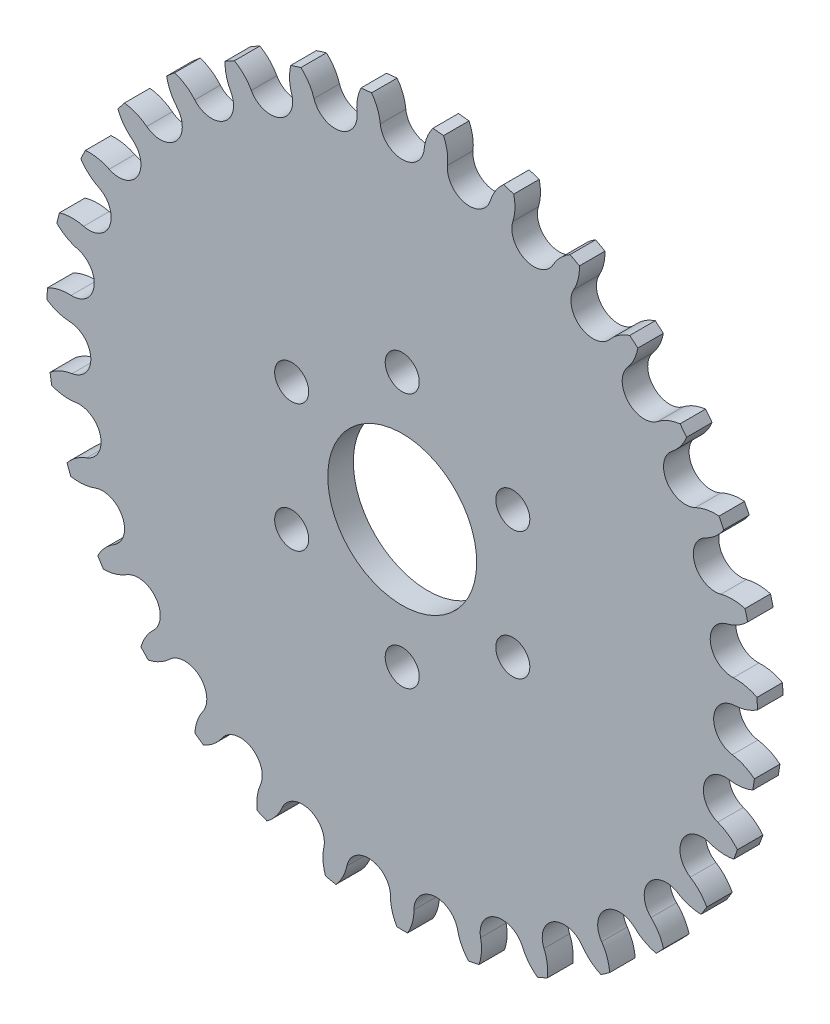
SolidWorks part; units mm, degrees
material "AISI 1020"
ref_plane "Спереди" through (0, 0, 0) normal (0, 0, 1) x (1, 0, 0)
ref_plane "Сверху" through (0, 0, 0) normal (0, 1, 0) x (1, 0, 0)
ref_plane "Справа" through (0, 0, 0) normal (1, 0, 0) x (0, 0, -1)
sketch "Эскиз1" plane through (0, 0, 0) normal (0, 0, 1) x (1, 0, 0)
  line L0 (0, 0) -> (0, 85) construction
  line L1 (0, 85) -> (15.8056, 83.5176) construction
  line L2 (15.8056, 83.5176) -> (0, 0) construction
  line L3 (15.8056, 83.5176) -> (49.3989, 83.5176)
  line L4 (0, 0) -> (0, 78.4584)
  line L5 (0, 78.4584) -> (15.7936, 76.8523)
  line L6 (15.7936, 76.8523) -> (0, 0)
  circle A0 centre (0, 0) radius 85 construction
  circle A1 centre (0, 78.4584) radius 5.08
  circle A2 centre (15.7936, 76.8523) radius 5.08
  dimension "D1" = 170
  dimension "D6" = 10.16
  dimension "D2" = 15.875
  dimension "D3" = 10.716
  dimension "D4" = 33.5932
  dimension "D5" = 11.613
sketch "Эскиз2" plane through (0, 0, 0) normal (0, 0, 1) x (1, 0, 0)
  line L0 (0, 0) -> (0, 73.2784)
  line L1 (0, 0) -> (14.7508, 71.7783)
  line L4 (15.7936, 76.8523) -> (0, 0) construction
  arc A0 (10.6401, 77.3764) -> (9.695, 82.9739) centre (0, 78.4584) ccw
  arc A1 (0, 83.5384) -> (16.8161, 81.8283) centre (0, 0) cw construction
  circle A2 centre (0, 78.4584) radius 5.08 construction
  circle A3 centre (15.7936, 76.8523) radius 5.08 construction
  circle A4 centre (0, 0) radius 85 construction
  circle A5 centre (0, 78.4584) radius 5.18
  arc A6 (0, 73.2784) -> (5.1534, 77.9343) centre (0, 78.4584) ccw
  arc A7 (7.206, 83.227) -> (5.1534, 77.9343) centre (15.7936, 76.8523) ccw
  circle A8 centre (15.7936, 76.8523) radius 5.18
  arc A9 (10.6401, 77.3764) -> (14.7508, 71.7783) centre (15.7936, 76.8523) ccw
  arc A10 (7.206, 83.227) -> (9.695, 82.9739) centre (0, 0) cw
  dimension "D1" = 0.1
  dimension "D2" = 0.1
extrude "Бобышка-Вытянуть1" add sketch "Эскиз2" along normal blind 6
pattern_circular "Круговой массив1" count 31 over 360 about axis through (0, 0, 0) along (0, 0, 1) of "Бобышка-Вытянуть1"
sketch "Эскиз3" plane through (0, 0, 6) normal (0, 0, 1) x (1, 0, 0)
  line L0 (0, 0) -> (0, 30) construction
  line L1 (0, 0) -> (25.9808, 15) construction
  circle A0 centre (0, 0) radius 17.5
  circle A1 centre (0, 0) radius 30 construction
  circle A2 centre (0, 30) radius 4
  circle A3 centre (25.9808, 15) radius 4
  circle A4 centre (25.9808, -15) radius 4
  circle A5 centre (0, -30) radius 4
  circle A6 centre (-25.9808, -15) radius 4
  circle A7 centre (-25.9808, 15) radius 4
  dimension "D1" = 35
  dimension "D2" = 60
  dimension "D3" = 8
  dimension "D5" = 60
  dimension "D6" = 30
  dimension "D4" = 6
extrude "Вырез-Вытянуть1" cut sketch "Эскиз3" against normal through all
equation "\"D4@Эскиз1\"=360/\"D3@Эскиз1\""
equation "\"D5@Эскиз1\"=360/31"
